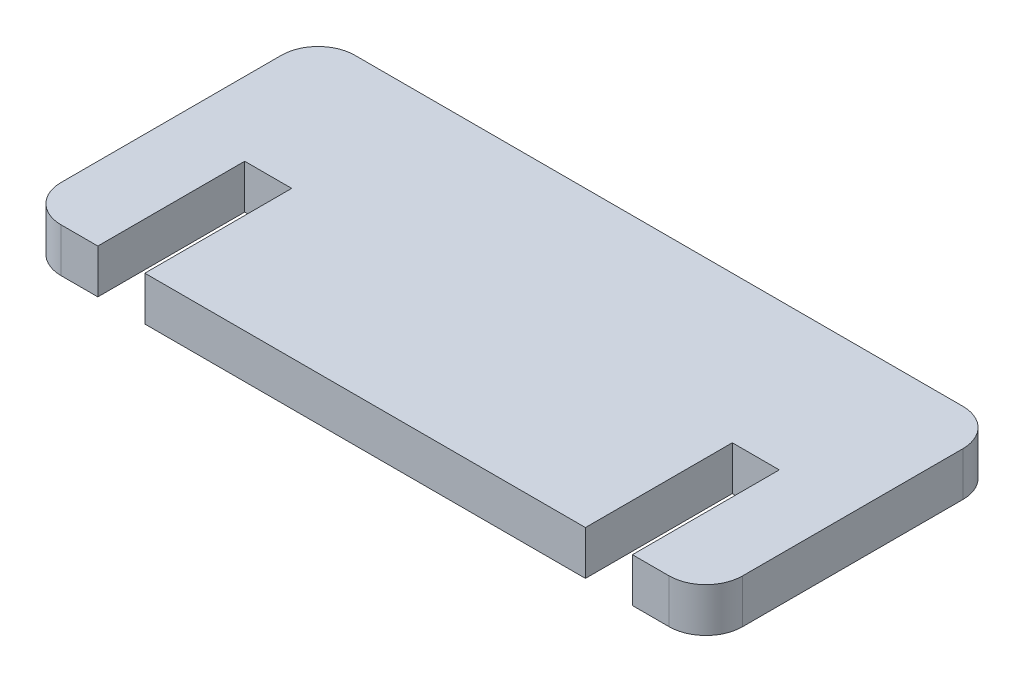
SolidWorks part; units mm, degrees
ref_plane "Front" through (0, 0, 0) normal (0, 0, 1) x (1, 0, 0)
ref_plane "Top" through (0, 0, 0) normal (0, 1, 0) x (1, 0, 0)
ref_plane "Right" through (0, 0, 0) normal (1, 0, 0) x (0, 0, -1)
sketch "草图1" plane through (0, 0, 0) normal (0, 1, 0) x (1, 0, 0)
  line L0 (15, 10) -> (20.7, 10)
  line L1 (-15, 10) -> (15, 10)
  line L2 (-15, 0) -> (-15, -10)
  line L3 (-15, -10) -> (15, -10)
  line L4 (15, 0) -> (15, -10)
  line L5 (0, -10) -> (0, 10) construction
  line L6 (-15, 0) -> (15, 0) construction
  line L7 (23.2, 7.5) -> (23.2, -7.5)
  line L8 (20.7, -10) -> (18.2, -10)
  line L9 (18.2, -10) -> (18.2, 0)
  line L10 (18.2, 0) -> (15, 0)
  line L11 (-18.2, 0) -> (-15, 0)
  line L12 (-18.2, -10) -> (-18.2, 0)
  line L13 (-20.7, -10) -> (-18.2, -10)
  line L14 (-23.2, 7.5) -> (-23.2, -7.5)
  line L15 (-15, 10) -> (-20.7, 10)
  arc A2 (23.2, -7.5) -> (20.7, -10) centre (20.7, -7.5) cw
  arc A3 (20.7, 10) -> (23.2, 7.5) centre (20.7, 7.5) cw
  arc A4 (-23.2, -7.5) -> (-20.7, -10) centre (-20.7, -7.5) ccw
  arc A5 (-20.7, 10) -> (-23.2, 7.5) centre (-20.7, 7.5) ccw
  point P0 (0, 0)
  point P17 (23.2, -10)
  point P24 (0, 0)
  dimension "D5" = 10
  dimension "D11" = 2.5
  dimension "D1" = 30
  dimension "D2" = 20
  dimension "D3" = 3.2
  dimension "D4" = 5
  dimension "D6" = 10
extrude "凸台-拉伸1" add sketch "草图1" along normal blind 3
